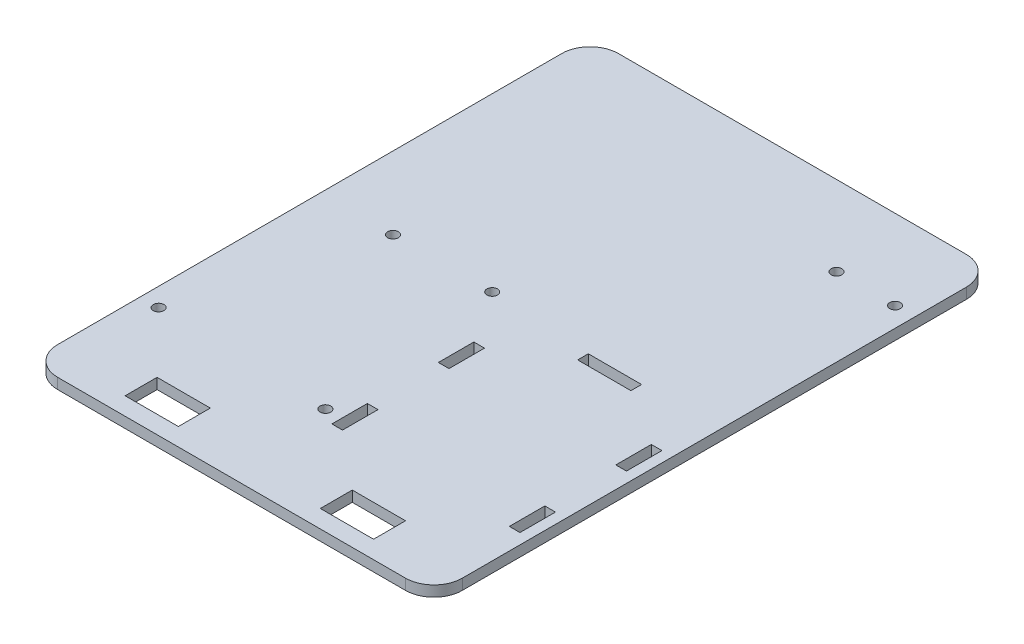
SolidWorks part; units mm, degrees
material "ABS PC"
ref_plane "Front Plane" through (0, 0, 0) normal (0, 0, 1) x (1, 0, 0)
ref_plane "Top Plane" through (0, 0, 0) normal (0, 1, 0) x (1, 0, 0)
ref_plane "Right Plane" through (0, 0, 0) normal (1, 0, 0) x (0, 0, -1)
sketch "Sketch1" plane through (0, 0, 0) normal (0, 1, 0) x (1, 0, 0)
  line L0 (0, 79) -> (0, 0) construction
  line L1 (-49, 79) -> (49, 79)
  line L2 (-57, 71) -> (-57, -71)
  line L3 (-49, -79) -> (49, -79)
  line L4 (57, 71) -> (57, -71)
  line L5 (0, 0) -> (0, -79) construction
  arc A0 (57, 71) -> (49, 79) centre (49, 71) ccw
  arc A1 (57, -71) -> (49, -79) centre (49, -71) cw
  arc A2 (-49, -79) -> (-57, -71) centre (-49, -71) cw
  arc A3 (-57, 71) -> (-49, 79) centre (-49, 71) cw
  dimension "D1" = 8
  dimension "D2" = 158
  dimension "D3" = 114
extrude "Boss-Extrude1" add sketch "Sketch1" along normal blind 3
sketch "Sketch2" plane through (0, 3, 0) normal (0, 1, 0) x (1, 0, 0)
  line L0 (4, -20) -> (4, -50) construction
  line L1 (1, -5) -> (4, -5) construction
  line L2 (1, -5) -> (1, -20) construction
  line L3 (1, -20) -> (4, -20) construction
  line L4 (4, -5) -> (4, -20) construction
  line L5 (1, -50) -> (4, -50) construction
  line L6 (1, -50) -> (1, -65) construction
  line L7 (1, -65) -> (4, -65) construction
  line L8 (4, -50) -> (4, -65) construction
  line L9 (20, 3) -> (35, 3) construction
  line L10 (20, 3) -> (20, 0) construction
  line L11 (20, 0) -> (35, 0) construction
  line L12 (35, 3) -> (35, 0) construction
  line L13 (51, -5) -> (54, -5) construction
  line L14 (51, -5) -> (51, -20) construction
  line L15 (51, -20) -> (54, -20) construction
  line L16 (54, -5) -> (54, -20) construction
  line L17 (51, -50) -> (54, -50) construction
  line L18 (51, -50) -> (51, -65) construction
  line L19 (51, -65) -> (54, -65) construction
  line L20 (54, -50) -> (54, -65) construction
  line L21 (20, -70) -> (35, -70) construction
  line L22 (20, -70) -> (20, -73) construction
  line L23 (20, -73) -> (35, -73) construction
  line L24 (35, -70) -> (35, -73) construction
  line L25 (51, -20) -> (51, -50) construction
  line L26 (4, -35) -> (51, -35) construction
  line L27 (27.5, 0) -> (27.5, -35) construction
  line L28 (27.5, -35) -> (27.5, -70) construction
  line L30 (-49, -79) -> (49, -79) construction
  line L31 (-20, -73) -> (20, -73) construction
  line L32 (-35, -70) -> (-20, -70) construction
  line L33 (-35, -70) -> (-35, -73) construction
  line L34 (-35, -73) -> (-20, -73) construction
  line L35 (-20, -70) -> (-20, -73) construction
  line L36 (0, 0) -> (0, -73) construction
  line L37 (57, -71) -> (57, 71) construction
  circle A0 centre (-36.56, 3.04) radius 1.5
  circle A1 centre (-8.62, 3.04) radius 1.5
  circle A2 centre (-51.8, -47.76) radius 1.5
  circle A3 centre (-3.54, -49.03) radius 1.5
  circle A4 centre (-36.56, 3.04) radius 1.5 construction
  circle A5 centre (-8.62, 3.04) radius 1.5 construction
  circle A6 centre (-3.54, -49.03) radius 1.5 construction
  circle A7 centre (-51.8, -47.76) radius 1.5 construction
  circle A8 centre (34.95, 56.46) radius 1.5
  circle A9 centre (51.46, 56.46) radius 1.5
  circle A10 centre (51.46, 56.46) radius 0.879 construction
  circle A11 centre (34.95, 56.46) radius 0.879 construction
  dimension "D3" = 3
  dimension "D1" = 3
  dimension "D2" = 15
  dimension "D4" = 47
  dimension "D5" = 70
  dimension "D6" = 30
  dimension "D7" = 3
  dimension "D8" = 6
  dimension "D9" = 40
extrude "Cut-Extrude1" cut sketch "Sketch2" against normal through all
sketch "Sketch3" plane through (0, 0, 0) normal (0, -1, 0) x (-1, 0, 0)
  line L1 (35, -74) -> (20, -74)
  line L2 (35, -74) -> (35, -65)
  line L3 (35, -65) -> (20, -65)
  line L4 (20, -74) -> (20, -65)
  line L5 (-20, -74) -> (-35, -74)
  line L6 (-20, -74) -> (-20, -65)
  line L7 (-20, -65) -> (-35, -65)
  line L8 (-35, -74) -> (-35, -65)
  line L9 (-1, -51.75) -> (-4, -51.75)
  line L10 (-1, -51.75) -> (-1, -41.75)
  line L11 (-1, -41.75) -> (-4, -41.75)
  line L12 (-4, -51.75) -> (-4, -41.75)
  line L13 (-1, -21.75) -> (-4, -21.75)
  line L14 (-1, -21.75) -> (-1, -11.75)
  line L15 (-1, -11.75) -> (-4, -11.75)
  line L16 (-4, -21.75) -> (-4, -11.75)
  line L17 (-20, -1.5) -> (-35, -1.5)
  line L18 (-20, -1.5) -> (-20, 1.5)
  line L19 (-20, 1.5) -> (-35, 1.5)
  line L20 (-35, -1.5) -> (-35, 1.5)
  line L21 (-51, -11.75) -> (-54, -11.75)
  line L22 (-51, -11.75) -> (-51, -21.75)
  line L23 (-51, -21.75) -> (-54, -21.75)
  line L24 (-54, -11.75) -> (-54, -21.75)
  line L25 (-51, -41.75) -> (-54, -41.75)
  line L26 (-51, -41.75) -> (-51, -51.75)
  line L27 (-51, -51.75) -> (-54, -51.75)
  line L28 (-54, -41.75) -> (-54, -51.75)
extrude "Cut-Extrude2" cut sketch "Sketch3" against normal through all
